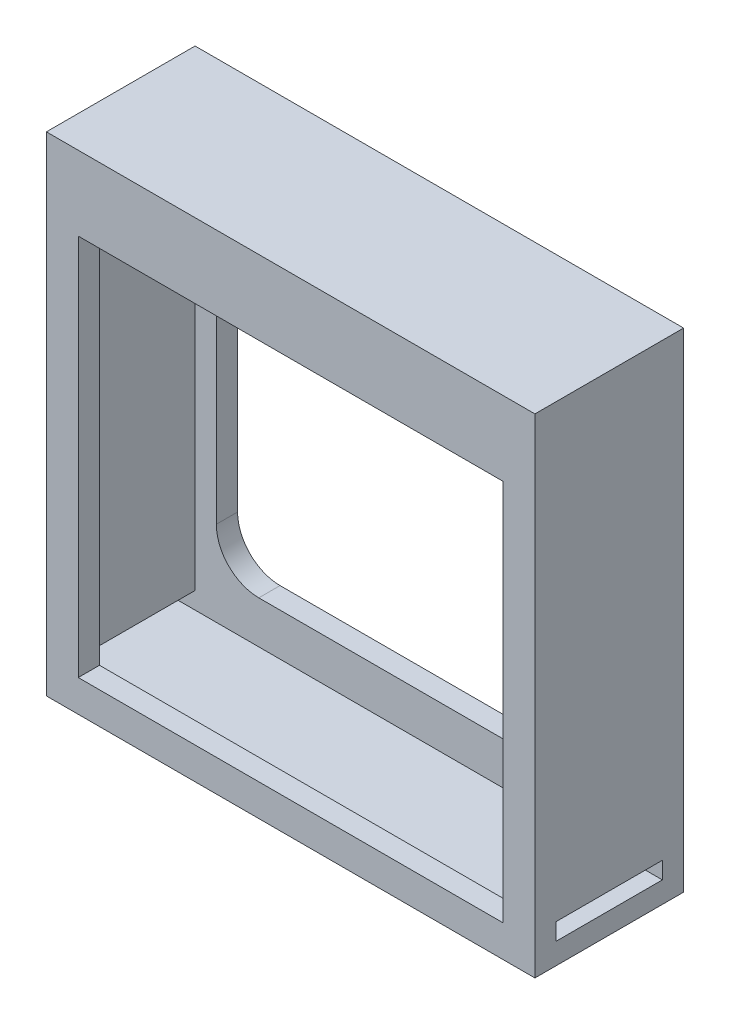
SolidWorks part; units mm, degrees
ref_plane "Front Plane" through (0, 0, 0) normal (0, 0, 1) x (1, 0, 0)
ref_plane "Top Plane" through (0, 0, 0) normal (0, 1, 0) x (1, 0, 0)
ref_plane "Right Plane" through (0, 0, 0) normal (1, 0, 0) x (0, 0, -1)
sketch "Sketch1" plane through (0, 0, 0) normal (0, 0, 1) x (1, 0, 0)
  line L1 (-57.5, -57.5) -> (57.5, -57.5)
  line L2 (-57.5, -57.5) -> (-57.5, 57.5)
  line L3 (-57.5, 57.5) -> (57.5, 57.5)
  line L4 (57.5, -57.5) -> (57.5, 57.5)
  line L5 (-57.5, -57.5) -> (57.5, 57.5) construction
  line L6 (-57.5, 57.5) -> (57.5, -57.5) construction
  point P0 (0, 0)
  dimension "D1" = 115
  dimension "D2" = 115
extrude "Boss-Extrude1" add sketch "Sketch1" along normal blind 35
sketch "Sketch4" plane through (0, 0, 35) normal (0, 0, 1) x (1, 0, 0)
  line L0 (-50, 40) -> (50, 40)
  line L1 (-50, -50) -> (50, -50)
  line L2 (-50, -50) -> (-50, 50)
  line L3 (-50, 50) -> (50, 50)
  line L4 (50, -50) -> (50, 50)
  line L5 (-50, -50) -> (50, 50) construction
  line L6 (-50, 50) -> (50, -50) construction
  point P0 (0, 0)
  dimension "D1" = 100
  dimension "D2" = 100
  dimension "D3" = 10
sketch "Sketch5" plane through (0, 0, 0) normal (0, 0, -1) x (-1, 0, 0)
  line L0 (-47.5, -42.5) -> (47.5, -42.5)
  line L1 (-47.5, -47.5) -> (47.5, -47.5)
  line L2 (-47.5, -47.5) -> (-47.5, 47.5)
  line L3 (-47.5, 47.5) -> (47.5, 47.5)
  line L4 (47.5, -47.5) -> (47.5, 47.5)
  line L5 (-47.5, -47.5) -> (47.5, 47.5) construction
  line L6 (-47.5, 47.5) -> (47.5, -47.5) construction
  line L7 (-57.5, -57.5) -> (-57.5, 57.5) construction
  line L8 (57.5, 57.5) -> (57.5, -57.5) construction
  line L9 (-57.5, 57.5) -> (57.5, 57.5) construction
  point P0 (0, 0)
  dimension "D1" = 95
  dimension "D2" = 10
  dimension "D3" = 5
  dimension "D4" = 10
  dimension "D5" = 95
  dimension "D6" = 10
shell "Shell2" thickness 5
extrude "Cut-Extrude1" cut sketch "Sketch4" against normal blind 30 contours L1 L4 L0 L2
extrude "Cut-Extrude2" cut sketch "Sketch5" against normal blind 30 contours L0 L4 L3 L2
fillet "Fillet1" radius 10 4 edges at (-47.5, -42.5, 2.5) (47.5, -42.5, 2.5) (-47.5, 47.5, 2.5) (47.5, 47.5, 2.5)
sketch "Sketch9" plane through (-52.5, 0, 0) normal (1, 0, 0) x (0, 0, -1)
  line L0 (-5, -48.5) -> (-30, -48.5)
  line L8 (-5, -52.5) -> (-5, 52.5)
  line L13 (-5, 52.5) -> (-30, 52.5)
  line L14 (-30, 52.5) -> (-30, -52.5)
  line L15 (-30, -52.5) -> (-5, -52.5)
  line L16 (-5, -52.5) -> (-5, 52.5)
  line L21 (-5, 52.5) -> (-30, 52.5)
  line L22 (-30, 52.5) -> (-30, -52.5)
  line L23 (-30, -52.5) -> (-5, -52.5)
  line M10 (-5, -52.5) -> (-5, 52.5)
  line M16 (-30, 52.5) -> (-30, -52.5)
  line M17 (-30, -52.5) -> (-5, -52.5)
  dimension "D2" = 4
  dimension "D1" = 0
extrude "Cut-Extrude3" cut sketch "Sketch9" against normal through all and the other way through all contours L0 M10 M16 M17
